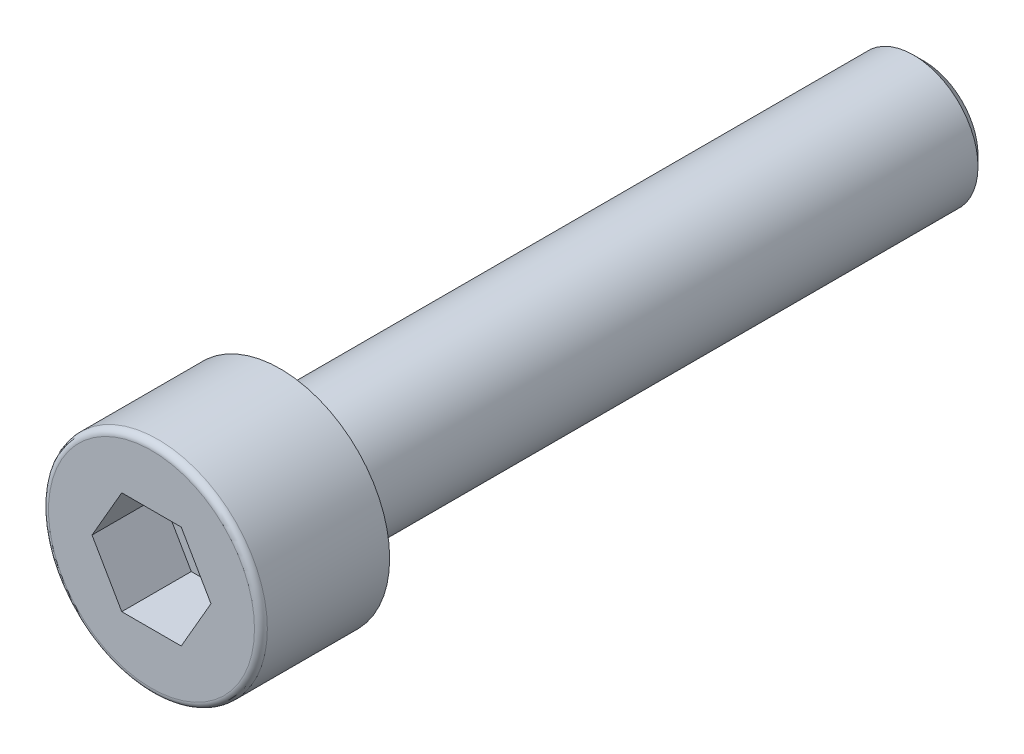
SolidWorks part; units mm, degrees
material "STAINLESS STEEL, 316S16"
ref_plane "Front Plane" through (0, 0, 0) normal (0, 0, 1) x (1, 0, 0)
ref_plane "Top Plane" through (0, 0, 0) normal (0, 1, 0) x (1, 0, 0)
ref_plane "Right Plane" through (0, 0, 0) normal (1, 0, 0) x (0, 0, -1)
sketch "Sketch1" plane through (0, 0, 0) normal (0, -1, 0) x (1, 0, 0)
  line L0 (0, 5) -> (0, -25) construction
  line L1 (0, -25) -> (-2.5, -25)
  line L2 (-2.5, -25) -> (-2.5, 0)
  line L3 (-2.5, 0) -> (-4.25, 0)
  line L4 (-4.25, 0) -> (-4.25, 4.75)
  line L5 (-4, 5) -> (0, 5)
  line L6 (0, 5) -> (0, -25)
  arc A0 (-4.25, 4.75) -> (-4, 5) centre (-4, 4.75) cw
  dimension "D4" = 0.25
  dimension "D1" = 5
  dimension "D2" = 8.5
  dimension "D3" = 5
  dimension "L" = 25
revolve "Revolve1" add sketch "Sketch1" angle 360 mid plane about L0
cosmetic thread "Thread" parameters "D1"=16, "D2"=4.11
sketch "Sketch2" plane through (0, 0, 5) normal (0, 0, 1) x (1, 0, 0)
  line L1 (2.3094, 0) -> (1.1547, 2)
  line L2 (1.1547, 2) -> (-1.1547, 2)
  line L3 (-1.1547, 2) -> (-2.3094, 0)
  line L4 (-2.3094, 0) -> (-1.1547, -2)
  line L5 (-1.1547, -2) -> (1.1547, -2)
  line L6 (1.1547, -2) -> (2.3094, 0)
  circle A0 centre (0, 0) radius 2 construction
  dimension "D1" = 4
extrude "Cut-Extrude1" cut sketch "Sketch2" against normal blind 2.7
chamfer "Chamfer1" distance 0.4 angle 45 1 edges at (2.5, 0, -25)
equation "\"D4@Sketch1\" = (\"D1@Sketch1\"/2)/10"
